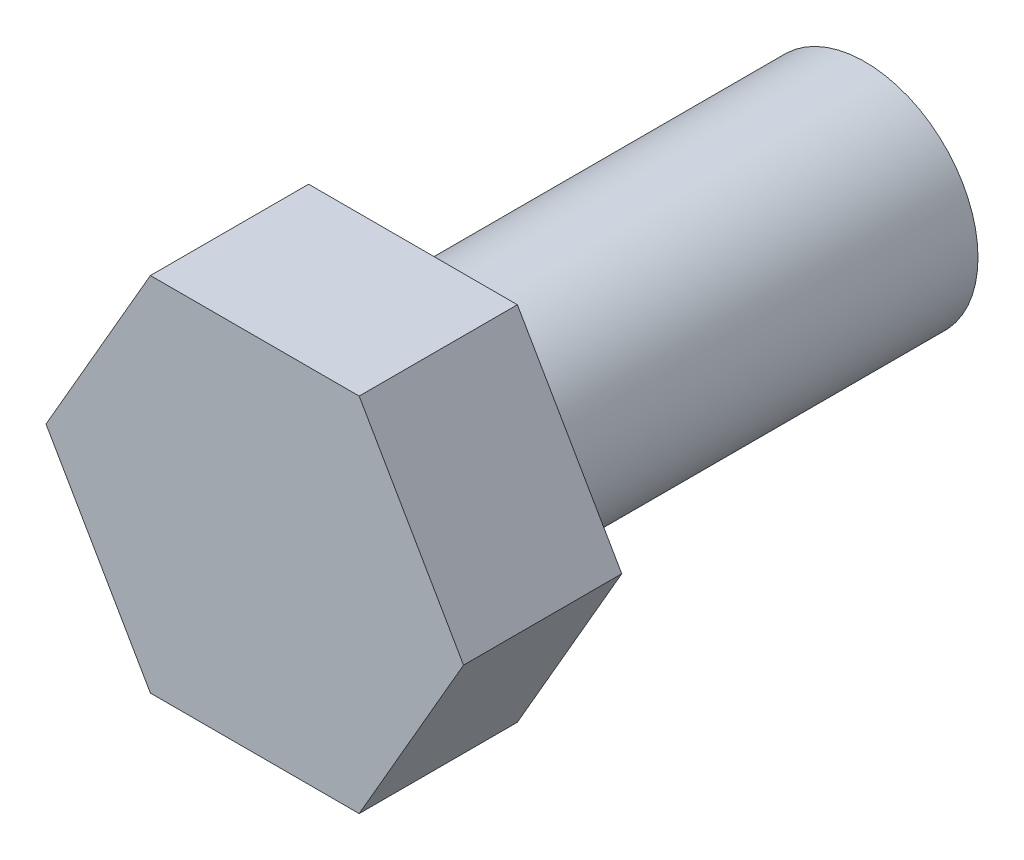
SolidWorks part; units mm, degrees
material "AISI 304"
ref_plane "Front Plane" through (0, 0, 0) normal (0, 0, 1) x (1, 0, 0)
ref_plane "Top Plane" through (0, 0, 0) normal (0, 1, 0) x (1, 0, 0)
ref_plane "Right Plane" through (0, 0, 0) normal (1, 0, 0) x (0, 0, -1)
sketch "Sketch1" plane through (0, 0, 0) normal (0, 0, 1) x (1, 0, 0)
  circle A0 centre (0, 0) radius 2.5
  dimension "D1" = 5
extrude "Extrude1" add sketch "Sketch1" against normal blind 10
cosmetic thread "Cosmetic Thread1" parameters "D1"=10, "D2"=6.5278
sketch "Sketch2" plane through (0, 0, 0) normal (0, 0, 1) x (1, 0, 0)
  line L1 (-2.3094, 4) -> (-4.6188, 0)
  line L2 (-4.6188, 0) -> (-2.3094, -4)
  line L3 (-2.3094, -4) -> (2.3094, -4)
  line L4 (2.3094, -4) -> (4.6188, 0)
  line L5 (4.6188, 0) -> (2.3094, 4)
  line L6 (2.3094, 4) -> (-2.3094, 4)
  circle A0 centre (0, 0) radius 4 construction
  dimension "D1" = 8
extrude "Extrude2" add sketch "Sketch2" along normal blind 3.5
